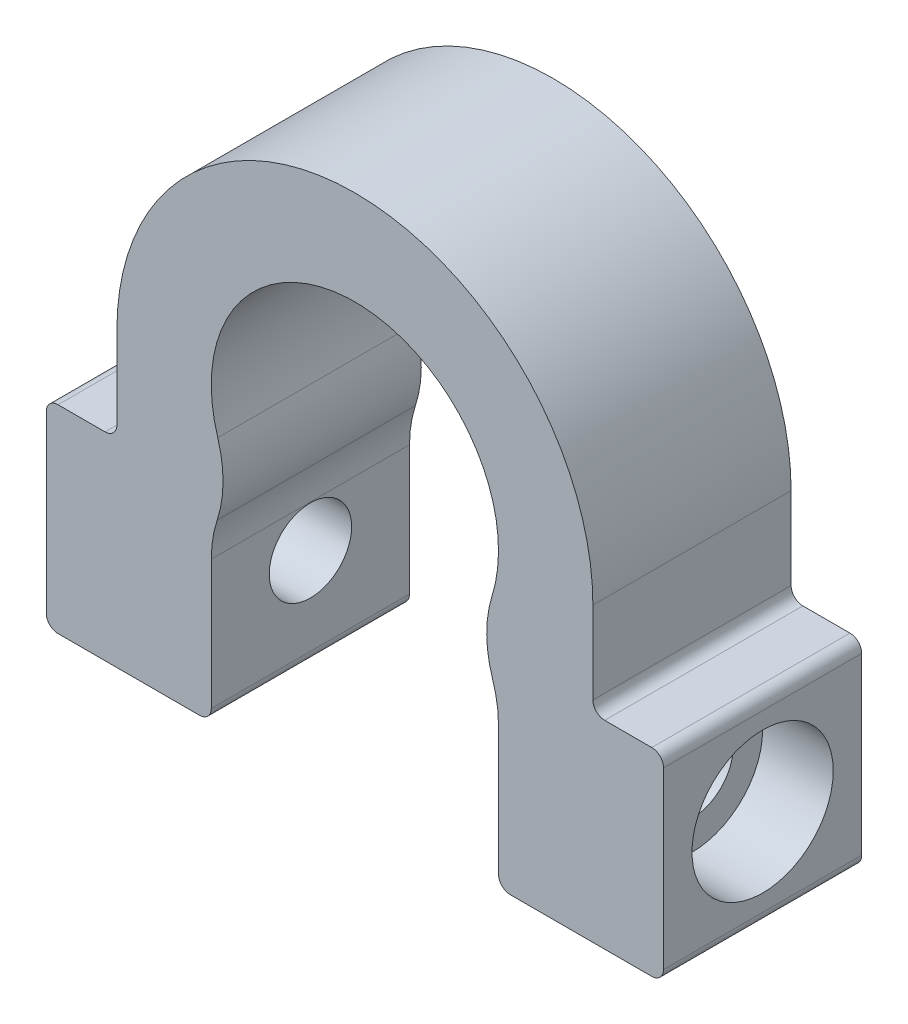
SolidWorks part; units mm, degrees
ref_plane "Front Plane" through (0, 0, 0) normal (0, 0, 1) x (1, 0, 0)
ref_plane "Top Plane" through (0, 0, 0) normal (0, 1, 0) x (1, 0, 0)
ref_plane "Right Plane" through (0, 0, 0) normal (1, 0, 0) x (0, 0, -1)
sketch "Sketch1" plane through (0, 0, 0) normal (0, 0, 1) x (1, 0, 0)
  line L3 (-6.1, -6.4164) -> (-6.1, -11.91)
  line L5 (6.1, -6.4164) -> (6.1, -11.91)
  line L14 (-10.11, 0) -> (-10.11, -3.49)
  line L16 (10.11, 0) -> (10.11, -3.49)
  line L19 (-10.61, -3.99) -> (-12.61, -3.99)
  line L20 (-13.11, -11.91) -> (-13.11, -4.49)
  line L22 (13.11, -11.91) -> (13.11, -4.49)
  line L23 (12.61, -3.99) -> (10.61, -3.99)
  line L25 (-12.61, -12.41) -> (-6.6, -12.41)
  line L26 (6.6, -12.41) -> (12.61, -12.41)
  arc A0 (5.8252, -1.8102) -> (-5.8252, -1.8102) centre (0, 0) ccw
  arc A1 (10.11, 0) -> (-10.11, 0) centre (0, 0) ccw
  arc A2 (-6.1, -6.4164) -> (-5.85, -4.8552) centre (-1.1, -6.4164) cw
  arc A3 (6.1, -6.4164) -> (5.85, -4.8552) centre (1.1, -6.4164) ccw
  arc A5 (-5.85, -4.8552) -> (-5.8252, -1.8102) centre (-10.6, -3.2939) ccw
  arc A6 (5.8252, -1.8102) -> (5.85, -4.8552) centre (10.6, -3.2939) ccw
  arc A7 (6.6, -12.41) -> (6.1, -11.91) centre (6.6, -11.91) cw
  arc A8 (-6.1, -11.91) -> (-6.6, -12.41) centre (-6.6, -11.91) cw
  arc A9 (-12.61, -3.99) -> (-13.11, -4.49) centre (-12.61, -4.49) ccw
  arc A10 (-12.61, -12.41) -> (-13.11, -11.91) centre (-12.61, -11.91) cw
  arc A11 (12.61, -12.41) -> (13.11, -11.91) centre (12.61, -11.91) ccw
  arc A12 (13.11, -4.49) -> (12.61, -3.99) centre (12.61, -4.49) ccw
  arc A13 (10.61, -3.99) -> (10.11, -3.49) centre (10.61, -3.49) cw
  arc A14 (-10.11, -3.49) -> (-10.61, -3.99) centre (-10.61, -3.49) cw
extrude "Boss-Extrude1" add sketch "Sketch1" along normal blind 8.42
sketch "Sketch2" plane through (13.11, 0, 0) normal (1, 0, 0) x (0, 0, -1)
  circle A0 centre (-4.21, -8.2) radius 1.75
extrude "Cut-Extrude1" cut sketch "Sketch2" against normal up to surface (26.22 mm away) up to face at (-13.11, -8.2, 4.21)
sketch "Sketch3" plane through (13.11, 0, 0) normal (1, 0, 0) x (0, 0, -1)
  circle A0 centre (-4.21, -8.2) radius 3
extrude "Cut-Extrude2" cut sketch "Sketch3" against normal blind 3
sketch "Sketch4" plane through (-13.11, 0, 0) normal (-1, 0, 0) x (0, 0, 1)
  line L1 (7.4432, -8.2) -> (5.8266, -5.4)
  line L2 (5.8266, -5.4) -> (2.5934, -5.4)
  line L3 (2.5934, -5.4) -> (0.9768, -8.2)
  line L4 (0.9768, -8.2) -> (2.5934, -11)
  line L5 (2.5934, -11) -> (5.8266, -11)
  line L6 (5.8266, -11) -> (7.4432, -8.2)
  circle A0 centre (4.21, -8.2) radius 2.8 construction
extrude "Cut-Extrude3" cut sketch "Sketch4" against normal blind 3
